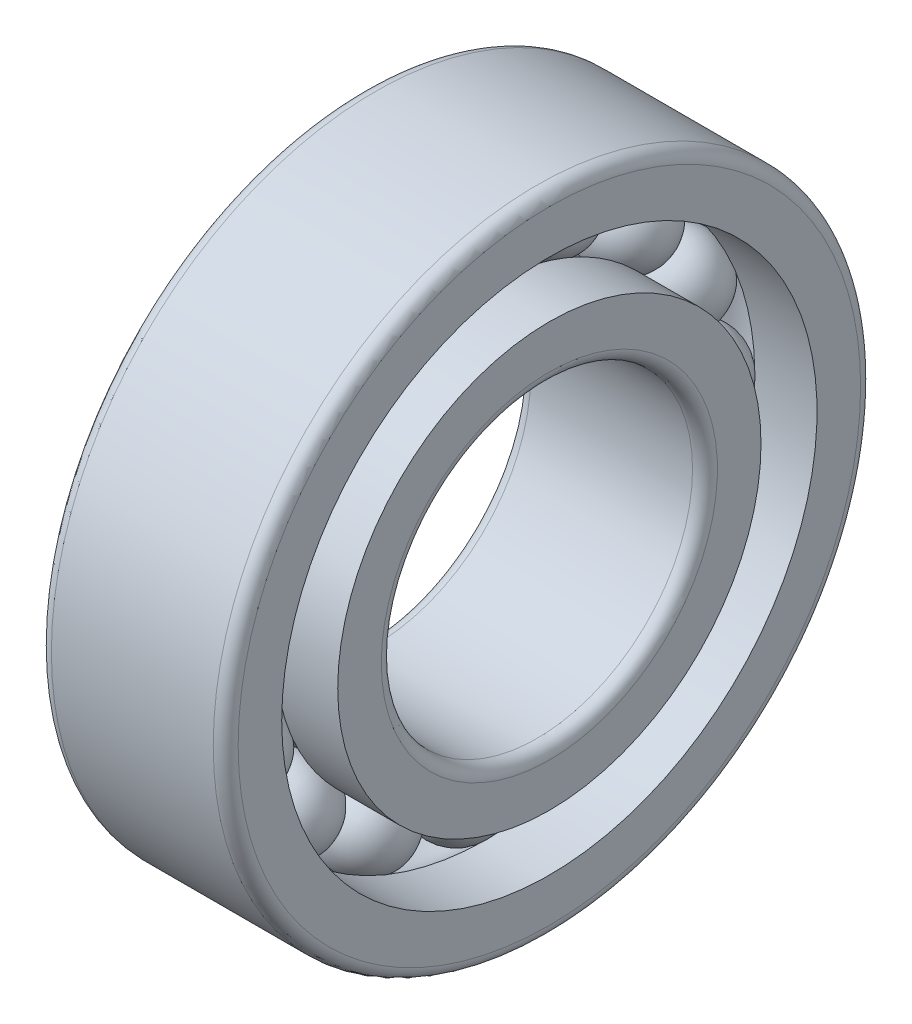
SolidWorks part; units mm, degrees
ref_plane "Front" through (0, 0, 0) normal (0, 0, 1) x (1, 0, 0)
ref_plane "Top" through (0, 0, 0) normal (0, 1, 0) x (1, 0, 0)
ref_plane "Right" through (0, 0, 0) normal (1, 0, 0) x (0, 0, -1)
sketch "Sketch1" plane through (0, 0, 0) normal (0, 0, 1) x (1, 0, 0)
  line L0 (-9.6833, 0) -> (9.8371, 0) construction
  line L1 (-3.375, 19.25) -> (3.375, 19.25)
  line L2 (-4.5966, 19.25) -> (4.6657, 19.25) construction
  arc A0 (3.375, 19.25) -> (-3.375, 19.25) centre (0, 19.25) ccw
  dimension "dia" = 6.75
  dimension "d0" = 38.5
revolve "Revolve1" add sketch "Sketch1" angle 360 about L2
sketch "Sketch2" plane through (0, 0, 0) normal (0, 0, 1) x (1, 0, 0)
  line L0 (-7.5, 17) -> (-7.5, 12.5)
  line L1 (-7.5, 12.5) -> (7.5, 12.5)
  line L2 (7.5, 12.5) -> (7.5, 17)
  line L3 (7.5, 17) -> (2.5021, 17)
  line L4 (-6.9714, 0) -> (8.1665, 0) construction
  line L5 (-6.7058, 19.25) -> (6.7058, 19.25) construction
  line L6 (-2.5021, 17) -> (-7.5, 17)
  arc A0 (-2.5021, 17) -> (2.5021, 17) centre (0, 19.25) ccw
  dimension "B" = 15
  dimension "B/2" = 7.5
  dimension "D5" = 6.73
  dimension "d" = 25
  dimension "D3" = 19.25
  dimension "D4" = 4.5
revolve "Revolve2" add sketch "Sketch2" angle 360 about L4
sketch "Sketch3" plane through (0, 0, 0) normal (0, 0, 1) x (1, 0, 0)
  line L0 (-8.7107, 0) -> (9.1288, 0) construction
  line L1 (-7.5, 26) -> (7.5, 26)
  line L2 (-7.5, 26) -> (-7.5, 21.5)
  line L3 (-7.5, 21.5) -> (-2.5021, 21.5)
  line L4 (7.5, 26) -> (7.5, 21.5)
  line L5 (-7.2948, 19.25) -> (7.2948, 19.25) construction
  line L6 (2.5021, 21.5) -> (7.5, 21.5)
  arc A0 (2.5021, 21.5) -> (-2.5021, 21.5) centre (0, 19.25) ccw
  dimension "D1" = 6.73
  dimension "DD" = 52
  dimension "B" = 15
  dimension "D4" = 19.25
  dimension "D5" = 4.5
  dimension "B/2" = 7.5
revolve "Revolve3" add sketch "Sketch3" angle 360 about L0
pattern_circular "Circular-Pattern1" count 16 over 360 about axis through (0, 0, 0) along (1, 0, 0) of "Revolve1"
fillet "Fillet1" radius 1 4 edges at (-7.5, 0, 12.5) (-7.5, 0, 26) (7.5, 0, 26) (7.5, 0, 12.5)
scale "缩放比例1" scale about origin uniform scaling yes scale factor 0.25
equation "\"d0@Sketch1\" = ( \"DD@Sketch3\" + \"d@Sketch2\" )  / 2"
equation "\"dia@Sketch1\" =  ( \"DD@Sketch3\" - \"d@Sketch2\" )  / 4"
equation "\"D3@Sketch2\" = ( \"DD@Sketch3\" + \"d@Sketch2\" )  / 2 / 2"
equation "\"D4@Sketch2\" = ( \"DD@Sketch3\" - \"d@Sketch2\" )  / 6"
equation "\"D5@Sketch2\" = \"dia@Sketch1\" - 0.02"
equation "\"B/2@Sketch2\" = \"B@Sketch2\" / 2"
equation "\"D4@Sketch3\" = ( \"DD@Sketch3\" + \"d@Sketch2\" )  / 2 / 2"
equation "\"D5@Sketch3\" = ( \"DD@Sketch3\" - \"d@Sketch2\" )  / 6"
equation "\"B@Sketch3\" = \"B@Sketch2\""
equation "\"B/2@Sketch3\" = \"B@Sketch3\" / 2"
equation "\"D1@Sketch3\" = \"dia@Sketch1\" - 0.02"
equation "\"m@Circular-Pattern1\" = int( 3.14159265 / atn(( \"dia@Sketch1\" / 2) / sqr(( \"DD@Sketch3\" + \"d@Sketch2\" )  / 2 * ( \"DD@Sketch3\" + \"d@Sketch2\" )  / 2/4 - ( \"dia@Sketch1\" / 2) *  ( \"dia@Sketch1\" / 2))))-1"
